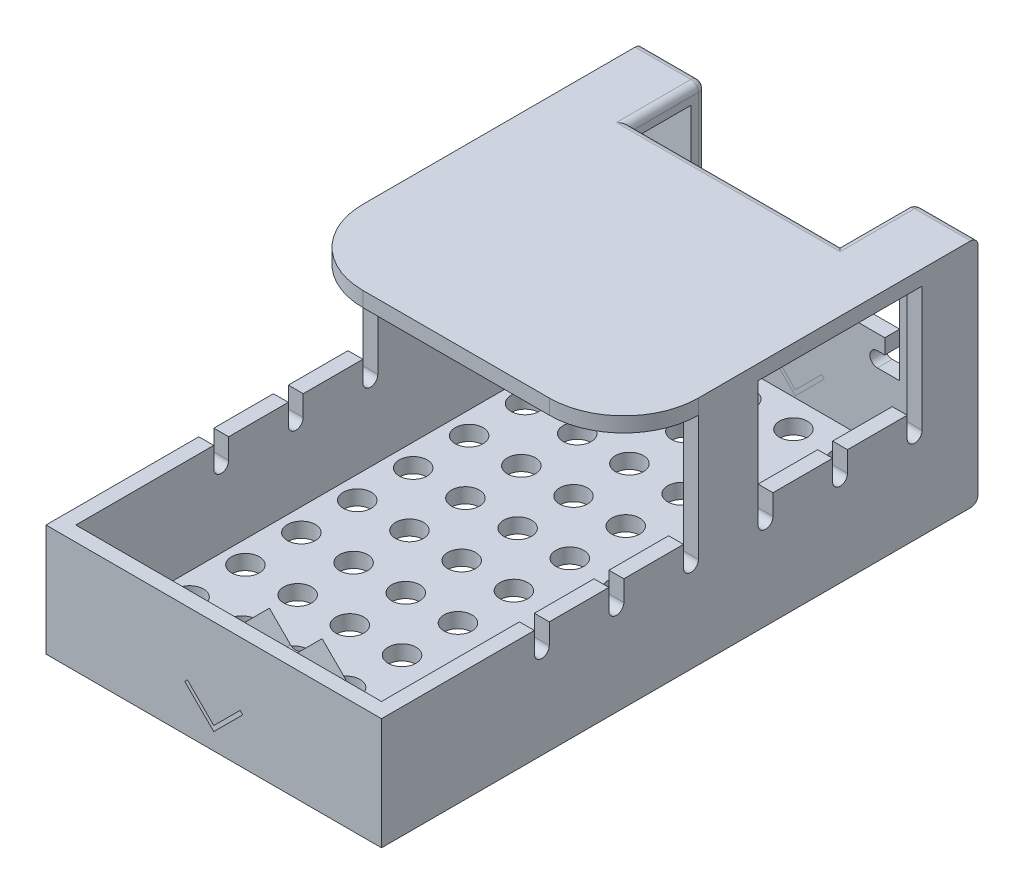
SolidWorks part; units mm, degrees
material "ABS"
ref_plane "Front Plane" through (0, 0, 0) normal (0, 0, 1) x (1, 0, 0)
ref_plane "Top Plane" through (0, 0, 0) normal (0, 1, 0) x (1, 0, 0)
ref_plane "Right Plane" through (0, 0, 0) normal (1, 0, 0) x (0, 0, -1)
sketch "Sketch1" plane through (0, 0, 0) normal (0, 0, 1) x (1, 0, 0)
  line L0 (0, 7.5111) -> (-8.9803, 16.4913)
  line L1 (-57.15, 0) -> (57.15, 0)
  line L2 (-57.15, 0) -> (-57.15, 38.1)
  line L3 (-57.15, 38.1) -> (57.15, 38.1)
  line L4 (57.15, 0) -> (57.15, 38.1)
  line L5 (-8.9803, 16.4913) -> (-9.8783, 15.5933)
  line L6 (-9.8783, 15.5933) -> (0, 5.715)
  line L7 (0, 5.715) -> (9.8783, 15.5933)
  line L8 (9.8783, 15.5933) -> (8.9803, 16.4913)
  line L9 (8.9803, 16.4913) -> (0, 7.5111)
  point P15 (0, 0)
  dimension "D1" = 12.7
  dimension "D2" = 1.27
  dimension "D3" = 5.715
  dimension "D4" = 45
  dimension "D5" = 114.3
  dimension "D6" = 38.1
extrude "Boss-Extrude1" add sketch "Sketch1" against normal blind 203.2
shell "Shell1" thickness 5.08
sketch "Sketch3" plane through (0, 0, 0) normal (1, 0, 0) x (0, 0, -1)
  line L0 (203.2, 38.1) -> (0, 38.1) construction
  line L1 (198.12, 38.1) -> (27.94, 38.1)
  line L2 (198.12, 38.1) -> (198.12, 5.08)
  line L3 (198.12, 5.08) -> (27.94, 5.08)
  line L4 (27.94, 38.1) -> (27.94, 5.08)
  line L5 (203.2, 0) -> (0, 0) construction
  line L6 (0, 0) -> (0, 38.1) construction
  line L7 (203.2, 0) -> (203.2, 38.1) construction
  dimension "D1" = 5.08
  dimension "D2" = 27.94
  dimension "D3" = 5.08
extrude "Cut-Extrude1" cut sketch "Sketch3" against normal up to next and the other way up to next
sketch "Sketch4" plane through (0, 0, -27.94) normal (0, 0, -1) x (-1, 0, 0)
  line L0 (0, 5.715) -> (-9.8783, 15.5933) construction
  line L11 (-9.8783, 15.5933) -> (-8.9803, 16.4913) construction
  line L12 (-8.9803, 16.4913) -> (0, 7.5111) construction
  line L13 (9.8783, 15.5933) -> (0, 5.715) construction
  line L14 (0, 7.5111) -> (8.9803, 16.4913) construction
  line L15 (8.9803, 16.4913) -> (9.8783, 15.5933) construction
  line L16 (0, 5.715) -> (-9.8783, 15.5933)
  line L17 (-9.8783, 15.5933) -> (-8.9803, 16.4913)
  line L18 (-8.9803, 16.4913) -> (0, 7.5111)
  line L19 (9.8783, 15.5933) -> (0, 5.715)
  line L20 (0, 7.5111) -> (8.9803, 16.4913)
  line L21 (8.9803, 16.4913) -> (9.8783, 15.5933)
extrude "Boss-Extrude2" add sketch "Sketch4" against normal blind 2.54
sketch "Sketch5" plane through (-57.15, 0, 0) normal (-1, 0, 0) x (0, 0, 1)
  line L0 (-203.2, 38.1) -> (0, 38.1) construction
  line L1 (-184.15, 38.1) -> (-179.07, 38.1)
  line L2 (-184.15, 38.1) -> (-184.15, 31.115)
  line L4 (-179.07, 38.1) -> (-179.07, 31.115)
  line L5 (-203.2, 38.1) -> (-203.2, 0) construction
  line L6 (-153.67, 38.1) -> (-153.67, 31.115)
  line L7 (-158.75, 38.1) -> (-153.67, 38.1)
  line L8 (-158.75, 38.1) -> (-158.75, 31.115)
  line L9 (-128.27, 38.1) -> (-128.27, 31.115)
  line L10 (-133.35, 38.1) -> (-128.27, 38.1)
  line L11 (-133.35, 38.1) -> (-133.35, 31.115)
  line L12 (-102.87, 38.1) -> (-102.87, 31.115)
  line L13 (-107.95, 38.1) -> (-102.87, 38.1)
  line L14 (-107.95, 38.1) -> (-107.95, 31.115)
  line L15 (-77.47, 38.1) -> (-77.47, 31.115)
  line L16 (-82.55, 38.1) -> (-77.47, 38.1)
  line L17 (-82.55, 38.1) -> (-82.55, 31.115)
  line L18 (-52.07, 38.1) -> (-52.07, 31.115)
  line L19 (-57.15, 38.1) -> (-52.07, 38.1)
  line L20 (-57.15, 38.1) -> (-57.15, 31.115)
  arc A0 (-184.15, 31.115) -> (-179.07, 31.115) centre (-181.61, 31.115) ccw
  arc A1 (-158.75, 31.115) -> (-153.67, 31.115) centre (-156.21, 31.115) ccw
  arc A2 (-133.35, 31.115) -> (-128.27, 31.115) centre (-130.81, 31.115) ccw
  arc A3 (-107.95, 31.115) -> (-102.87, 31.115) centre (-105.41, 31.115) ccw
  arc A4 (-82.55, 31.115) -> (-77.47, 31.115) centre (-80.01, 31.115) ccw
  arc A5 (-57.15, 31.115) -> (-52.07, 31.115) centre (-54.61, 31.115) ccw
  point P9 (-181.61, 28.575)
  dimension "D1" = 19.05
  dimension "D2" = 5.08
  dimension "D3" = 9.525
  dimension "D5" = 25.4
  dimension "D4" = 6
extrude "Cut-Extrude2" cut sketch "Sketch5" against normal through all both and the other way through all
sketch "Sketch6" plane through (0, 5.08, 0) normal (0, 1, 0) x (1, 0, 0)
  line L0 (52.07, 198.12) -> (-52.07, 198.12) construction
  line L1 (-52.07, 198.12) -> (-52.07, 5.08) construction
  circle A0 centre (-44.45, 188.595) radius 4.7625
  circle A1 centre (-26.67, 188.595) radius 4.7625
  circle A2 centre (-8.89, 188.595) radius 4.7625
  circle A3 centre (8.89, 188.595) radius 4.7625
  circle A4 centre (26.67, 188.595) radius 4.7625
  circle A5 centre (44.45, 188.595) radius 4.7625
  circle A6 centre (-26.67, 169.545) radius 4.7625
  circle A7 centre (-8.89, 169.545) radius 4.7625
  circle A8 centre (8.89, 169.545) radius 4.7625
  circle A9 centre (26.67, 169.545) radius 4.7625
  circle A10 centre (44.45, 169.545) radius 4.7625
  circle A11 centre (-26.67, 150.495) radius 4.7625
  circle A12 centre (-8.89, 150.495) radius 4.7625
  circle A13 centre (8.89, 150.495) radius 4.7625
  circle A14 centre (26.67, 150.495) radius 4.7625
  circle A15 centre (44.45, 150.495) radius 4.7625
  circle A16 centre (-26.67, 131.445) radius 4.7625
  circle A17 centre (-8.89, 131.445) radius 4.7625
  circle A18 centre (8.89, 131.445) radius 4.7625
  circle A19 centre (26.67, 131.445) radius 4.7625
  circle A20 centre (44.45, 131.445) radius 4.7625
  circle A21 centre (-26.67, 112.395) radius 4.7625
  circle A22 centre (-8.89, 112.395) radius 4.7625
  circle A23 centre (8.89, 112.395) radius 4.7625
  circle A24 centre (26.67, 112.395) radius 4.7625
  circle A25 centre (44.45, 112.395) radius 4.7625
  circle A26 centre (-26.67, 93.345) radius 4.7625
  circle A27 centre (-8.89, 93.345) radius 4.7625
  circle A28 centre (8.89, 93.345) radius 4.7625
  circle A29 centre (26.67, 93.345) radius 4.7625
  circle A30 centre (44.45, 93.345) radius 4.7625
  circle A31 centre (-26.67, 74.295) radius 4.7625
  circle A32 centre (-8.89, 74.295) radius 4.7625
  circle A33 centre (8.89, 74.295) radius 4.7625
  circle A34 centre (26.67, 74.295) radius 4.7625
  circle A35 centre (44.45, 74.295) radius 4.7625
  circle A36 centre (-26.67, 55.245) radius 4.7625
  circle A37 centre (-8.89, 55.245) radius 4.7625
  circle A38 centre (8.89, 55.245) radius 4.7625
  circle A39 centre (26.67, 55.245) radius 4.7625
  circle A40 centre (44.45, 55.245) radius 4.7625
  circle A41 centre (-26.67, 36.195) radius 4.7625
  circle A42 centre (-8.89, 36.195) radius 4.7625
  circle A43 centre (8.89, 36.195) radius 4.7625
  circle A44 centre (26.67, 36.195) radius 4.7625
  circle A45 centre (44.45, 36.195) radius 4.7625
  circle A46 centre (-44.45, 169.545) radius 4.7625
  circle A47 centre (-44.45, 150.495) radius 4.7625
  circle A48 centre (-44.45, 131.445) radius 4.7625
  circle A49 centre (-44.45, 112.395) radius 4.7625
  circle A50 centre (-44.45, 93.345) radius 4.7625
  circle A51 centre (-44.45, 74.295) radius 4.7625
  circle A52 centre (-44.45, 55.245) radius 4.7625
  circle A53 centre (-44.45, 36.195) radius 4.7625
  dimension "D3" = 9.525
  dimension "D1" = 9.525
  dimension "D2" = 7.62
  dimension "D4" = 6
  dimension "D5" = 9
extrude "Cut-Extrude3" cut sketch "Sketch6" against normal through all both and the other way through all
fillet "Fillet1" radius 2.54 3 edges at (0, 14.6953, -16.51) (6.5492, 5.08, -16.51) (-6.5492, 5.08, -16.51)
sketch "Sketch7" plane through (0, 0, -203.2) normal (0, 0, -1) x (-1, 0, 0)
  line L6 (-8.9803, 16.4913) -> (0, 7.5111) construction
  line L7 (-9.8783, 15.5933) -> (-8.9803, 16.4913) construction
  line L8 (0, 5.715) -> (-9.8783, 15.5933) construction
  line L9 (9.8783, 15.5933) -> (0, 5.715) construction
  line L10 (8.9803, 16.4913) -> (9.8783, 15.5933) construction
  line L11 (0, 7.5111) -> (8.9803, 16.4913) construction
  line L12 (-8.9803, 16.4913) -> (0, 7.5111)
  line L13 (-9.8783, 15.5933) -> (-8.9803, 16.4913)
  line L14 (0, 5.715) -> (-9.8783, 15.5933)
  line L15 (9.8783, 15.5933) -> (0, 5.715)
  line L16 (8.9803, 16.4913) -> (9.8783, 15.5933)
  line L17 (0, 7.5111) -> (8.9803, 16.4913)
extrude "Boss-Extrude3" add sketch "Sketch7" against normal up to surface (5.08 mm away) separate body
sketch "Sketch8" plane through (0, 0, -203.2) normal (0, 0, -1) x (-1, 0, 0)
  line L0 (-30.48, 38.1) -> (-30.48, 33.02)
  line L1 (-57.15, 38.1) -> (57.15, 38.1) construction
  line L2 (-35.56, 38.1) -> (-35.56, 27.94)
  line L3 (-35.56, 38.1) -> (-30.48, 38.1)
  line L4 (0, 20.955) -> (0, -20.955) construction
  line L8 (-30.48, 33.02) -> (-27.94, 33.02)
  line L9 (-35.56, 27.94) -> (-27.94, 27.94)
  line L10 (30.48, 33.02) -> (27.94, 33.02)
  line L11 (30.48, 38.1) -> (30.48, 33.02)
  line L12 (35.56, 38.1) -> (30.48, 38.1)
  line L13 (35.56, 38.1) -> (35.56, 27.94)
  line L14 (35.56, 27.94) -> (27.94, 27.94)
  arc A2 (-27.94, 33.02) -> (-27.94, 27.94) centre (-27.94, 30.48) cw
  arc A3 (27.94, 33.02) -> (27.94, 27.94) centre (27.94, 30.48) ccw
  dimension "D3" = 10.16
  dimension "D1" = 5.08
  dimension "D2" = 30.48
  dimension "D4" = 2.54
  dimension "D5" = 5.08
extrude "Cut-Extrude4" cut sketch "Sketch8" against normal up to surface (5.08 mm away)
sketch "Sketch10" plane through (0, 38.1, 0) normal (0, 1, 0) x (1, 0, 0)
  line L4 (-52.07, 128.27) -> (-57.15, 128.27)
  line L5 (-57.15, 128.27) -> (-57.15, 107.95)
  line L6 (35.56, 203.2) -> (35.56, 198.12)
  line L7 (35.56, 198.12) -> (52.07, 198.12)
  line L8 (52.07, 198.12) -> (52.07, 184.15)
  line L9 (52.07, 184.15) -> (57.15, 184.15)
  line L10 (57.15, 184.15) -> (57.15, 203.2)
  line L11 (57.15, 203.2) -> (35.56, 203.2)
  line L12 (35.56, 203.2) -> (35.56, 198.12)
  line L13 (35.56, 198.12) -> (52.07, 198.12)
  line L14 (52.07, 198.12) -> (52.07, 184.15)
  line L15 (52.07, 184.15) -> (57.15, 184.15)
  line L16 (57.15, 184.15) -> (57.15, 203.2)
  line L17 (57.15, 203.2) -> (35.56, 203.2)
  line L18 (-35.56, 198.12) -> (-35.56, 203.2)
  line L19 (-35.56, 203.2) -> (-57.15, 203.2)
  line L20 (-57.15, 203.2) -> (-57.15, 184.15)
  line L21 (-57.15, 184.15) -> (-52.07, 184.15)
  line L22 (-52.07, 184.15) -> (-52.07, 198.12)
  line L23 (-52.07, 198.12) -> (-35.56, 198.12)
  line L24 (-35.56, 198.12) -> (-35.56, 203.2)
  line L25 (-35.56, 203.2) -> (-57.15, 203.2)
  line L26 (-57.15, 203.2) -> (-57.15, 184.15)
  line L27 (-57.15, 184.15) -> (-52.07, 184.15)
  line L28 (-52.07, 184.15) -> (-52.07, 198.12)
  line L29 (-52.07, 198.12) -> (-35.56, 198.12)
  line L30 (-57.15, 107.95) -> (-52.07, 107.95)
  line L31 (-52.07, 107.95) -> (-52.07, 128.27)
  line L32 (-52.07, 128.27) -> (-57.15, 128.27)
  line L33 (-57.15, 128.27) -> (-57.15, 107.95)
  line L34 (-57.15, 107.95) -> (-52.07, 107.95)
  line L35 (-52.07, 107.95) -> (-52.07, 128.27)
  line L36 (57.15, 128.27) -> (52.07, 128.27)
  line L37 (52.07, 128.27) -> (52.07, 107.95)
  line L38 (52.07, 107.95) -> (57.15, 107.95)
  line L39 (57.15, 107.95) -> (57.15, 128.27)
  line L40 (57.15, 128.27) -> (52.07, 128.27)
  line L41 (52.07, 128.27) -> (52.07, 107.95)
  line L42 (52.07, 107.95) -> (57.15, 107.95)
  line L43 (57.15, 107.95) -> (57.15, 128.27)
  dimension "D1" = 0
  dimension "D2" = 0
  dimension "D3" = 0
  dimension "D4" = 0
extrude "Boss-Extrude4" add sketch "Sketch10" along normal blind 35.56
sketch "Sketch11" plane through (0, 0, -107.95) normal (0, 0, 1) x (1, 0, 0)
  line L0 (-57.15, 73.66) -> (-57.15, 78.74)
  line L1 (-57.15, 78.74) -> (57.15, 78.74)
  line L2 (57.15, 78.74) -> (57.15, 73.66)
  line L3 (-57.15, 73.66) -> (57.15, 73.66)
  dimension "D1" = 5.08
extrude "Boss-Extrude5" add sketch "Sketch11" against normal blind 95.25 and the other way blind 25.4
fillet "Fillet2" radius 2.54 2 edges at (0, 0, -203.2) (0, 78.74, -203.2)
sketch "Sketch12" plane through (0, 78.74, 0) normal (0, 1, 0) x (1, 0, 0)
  line L0 (0, -43.307) -> (0, 43.307) construction
  line L1 (35.56, 177.8) -> (-35.56, 177.8)
  line L2 (35.56, 177.8) -> (35.56, 203.2)
  line L3 (35.56, 203.2) -> (-35.56, 203.2)
  line L4 (-35.56, 177.8) -> (-35.56, 203.2)
  line L5 (35.56, 177.8) -> (-35.56, 203.2) construction
  line L6 (35.56, 203.2) -> (-35.56, 177.8) construction
  line L7 (-57.15, 203.2) -> (57.15, 203.2) construction
  point P0 (0, 190.5)
  dimension "D1" = 25.4
  dimension "D2" = 71.12
extrude "Cut-Extrude5" cut sketch "Sketch12" against normal up to surface (5.08 mm away) up to face at (0, 73.66, -152.273)
fillet "Fillet3" radius 2.54 7 edges at (-35.56, 52.07, -203.2) (-35.56, 77.9961, -202.4561) (35.56, 52.07, -203.2) (35.56, 77.9961, -202.4561) (-35.56, 78.74, -189.23) (0, 78.74, -177.8) (35.56, 78.74, -189.23)
fillet "Fillet4" radius 25.4 2 edges at (-57.15, 76.2, -82.55) (57.15, 76.2, -82.55)
